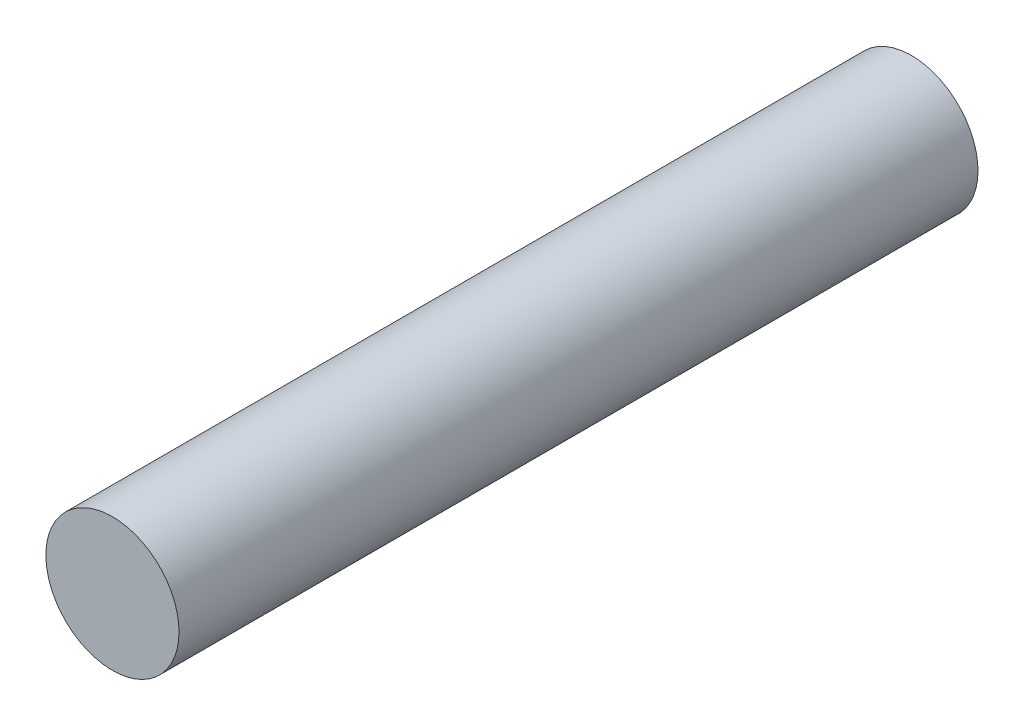
SolidWorks part; units mm, degrees
ref_plane "Front Plane" through (0, 0, 0) normal (0, 0, 1) x (1, 0, 0)
ref_plane "Top Plane" through (0, 0, 0) normal (0, 1, 0) x (1, 0, 0)
ref_plane "Right Plane" through (0, 0, 0) normal (1, 0, 0) x (0, 0, -1)
sketch "Sketch1" plane through (0, 0, 0) normal (0, 0, 1) x (1, 0, 0)
  circle A0 centre (0, 0) radius 4
extrude "Boss-Extrude1" add sketch "Sketch1" along normal blind 48
